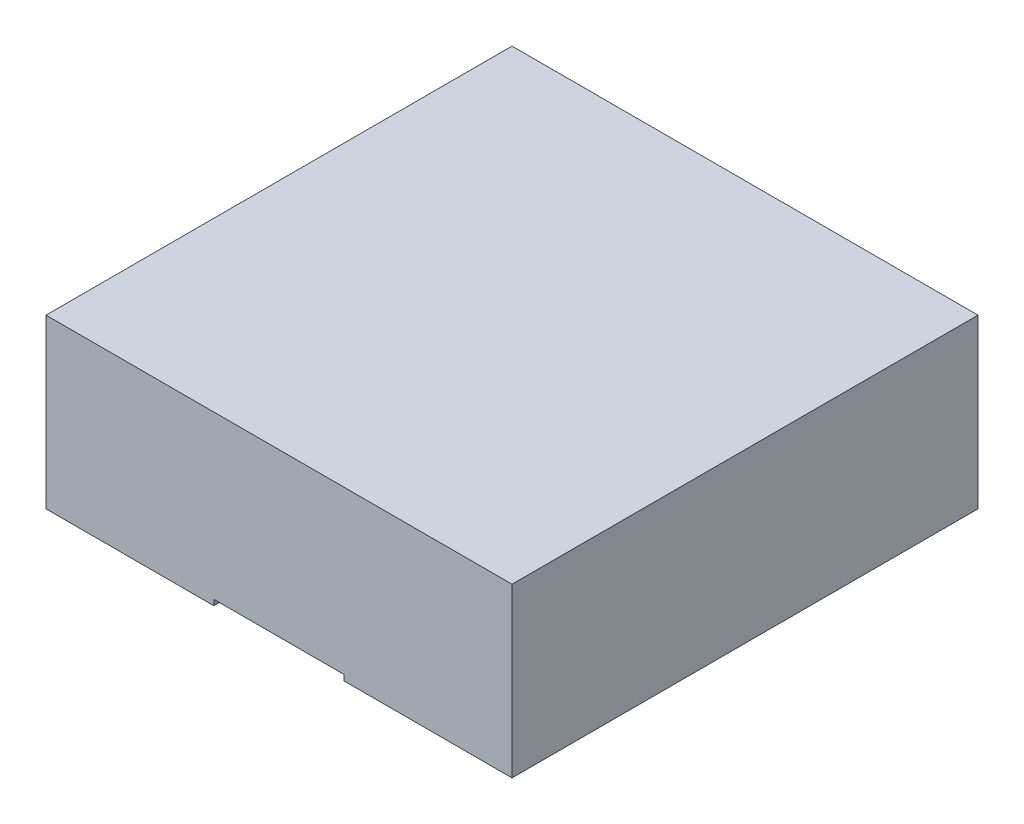
SolidWorks part; units mm, degrees
material "PTFE (general)"
ref_plane "Front Plane" through (0, 0, 0) normal (0, 0, 1) x (1, 0, 0)
ref_plane "Top Plane" through (0, 0, 0) normal (0, 1, 0) x (1, 0, 0)
ref_plane "Right Plane" through (0, 0, 0) normal (1, 0, 0) x (0, 0, -1)
sketch "Sketch1" plane through (0, 0, 0) normal (0, 1, 0) x (1, 0, 0)
  line L1 (-12.5, -12.5) -> (12.5, -12.5)
  line L2 (-12.5, -12.5) -> (-12.5, 12.5)
  line L3 (-12.5, 12.5) -> (12.5, 12.5)
  line L4 (12.5, -12.5) -> (12.5, 12.5)
  line L5 (-12.5, -12.5) -> (12.5, 12.5) construction
  line L6 (-12.5, 12.5) -> (12.5, -12.5) construction
  point P0 (0, 0)
  dimension "D1" = 25
extrude "Boss-Extrude1" add sketch "Sketch1" along normal mid plane 9
sketch "Sketch2" plane through (0, -4.5, 0) normal (0, -1, 0) x (1, 0, 0)
  line L0 (-12.5, 12.5) -> (12.5, 12.5) construction
  line L1 (-3.5, 12.5) -> (3.5, 12.5)
  line L2 (-3.5, 12.5) -> (-3.5, -4)
  line L3 (-3.5, -4) -> (3.5, -4)
  line L4 (3.5, 12.5) -> (3.5, -4)
  point P6 (0, -4)
  dimension "D1" = 16.5
  dimension "D2" = 7
extrude "Cut-Extrude1" cut sketch "Sketch2" against normal blind 0.3
